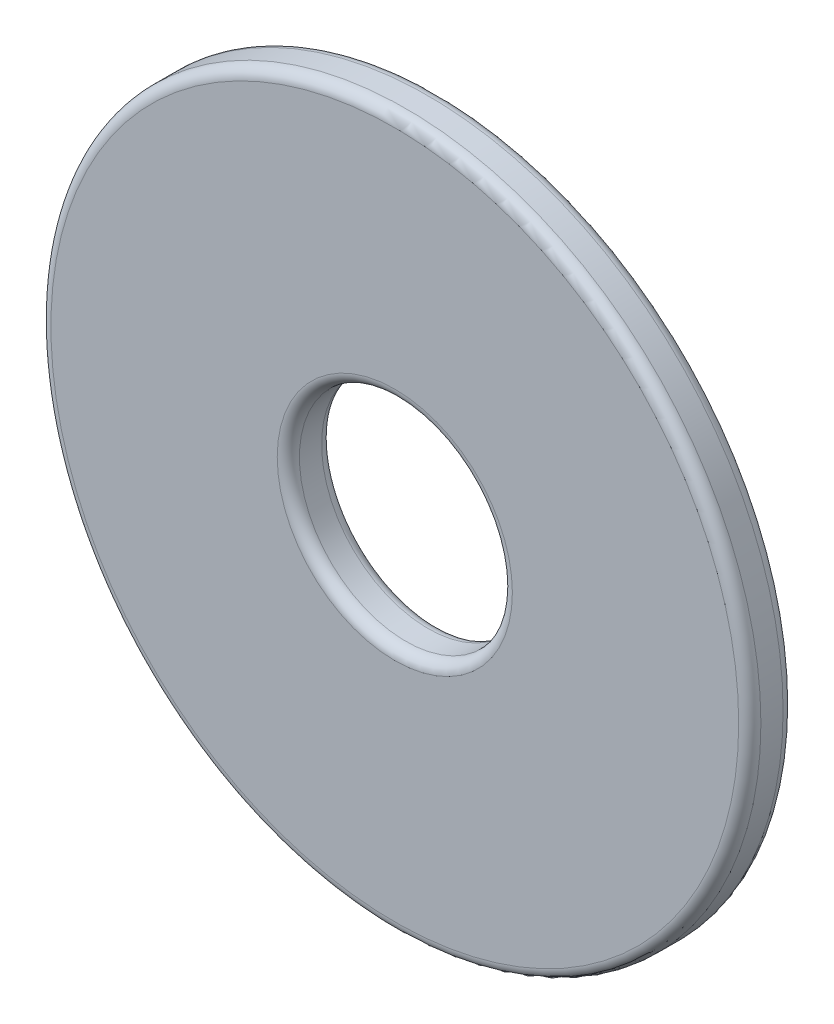
SolidWorks part; units mm, degrees
material "Wrought Stainless Steel"
ref_plane "Front Plane" through (0, 0, 0) normal (0, 0, 1) x (1, 0, 0)
ref_plane "Top Plane" through (0, 0, 0) normal (0, 1, 0) x (1, 0, 0)
ref_plane "Right Plane" through (0, 0, 0) normal (1, 0, 0) x (0, 0, -1)
sketch "Sketch1" plane through (0, 0, 0) normal (0, 0, 1) x (1, 0, 0)
  circle A0 centre (0, 0) radius 12.7
  circle A1 centre (0, 0) radius 3.81
  dimension "D1" = 25.4
  dimension "D2" = 7.62
extrude "Boss-Extrude1" add sketch "Sketch1" along normal blind 1.5875
fillet "Fillet1" radius 0.3969 4 edges at (3.81, 0, 0) (12.7, 0, 0) (3.81, 0, 1.5875) (12.7, 0, 1.5875)
